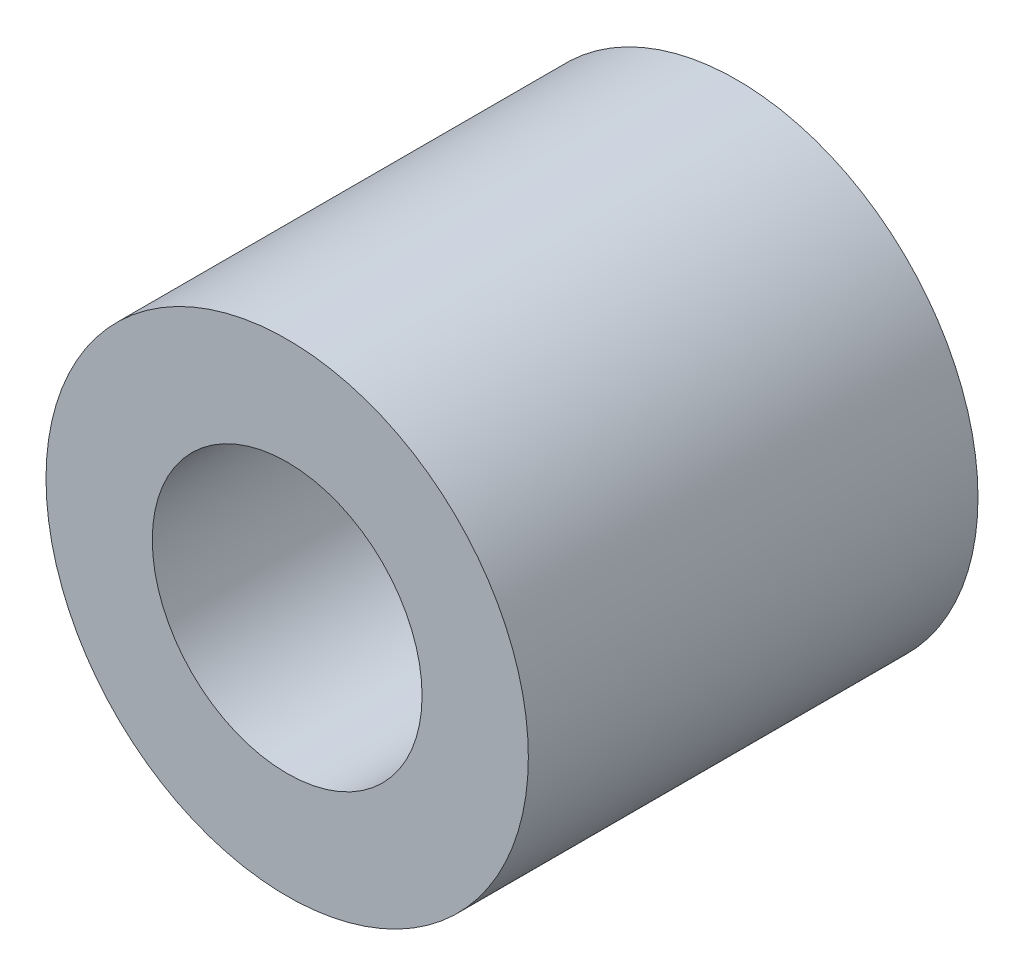
SolidWorks part; units mm, degrees
ref_plane "Front Plane" through (0, 0, 0) normal (0, 0, 1) x (1, 0, 0)
ref_plane "Top Plane" through (0, 0, 0) normal (0, 1, 0) x (1, 0, 0)
ref_plane "Right Plane" through (0, 0, 0) normal (1, 0, 0) x (0, 0, -1)
sketch "Sketch1" plane through (0, 0, 0) normal (0, 0, 1) x (1, 0, 0)
  circle A0 centre (0, 0) radius 1.65
  circle A1 centre (0, 0) radius 2.95
  dimension "D1" = 3.3
  dimension "D2" = 1.3
extrude "Boss-Extrude1" add sketch "Sketch1" along normal blind 5.5
